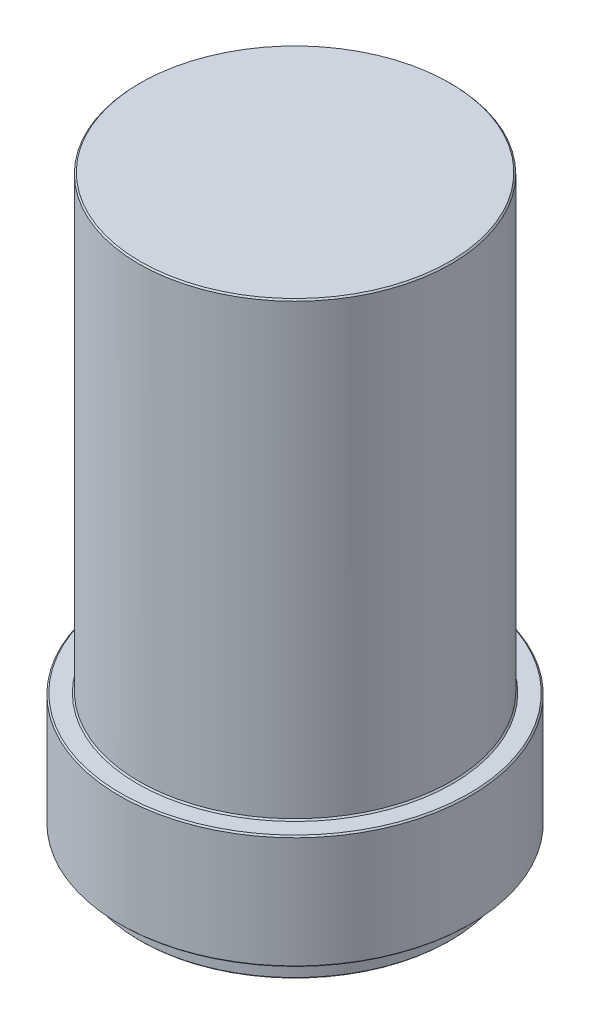
SolidWorks part; units mm, degrees
ref_plane "Front Plane" through (0, 0, 0) normal (0, 0, 1) x (1, 0, 0)
ref_plane "Top Plane" through (0, 0, 0) normal (0, 1, 0) x (1, 0, 0)
ref_plane "Right Plane" through (0, 0, 0) normal (1, 0, 0) x (0, 0, -1)
sketch "Sketch1" plane through (0, 0, 0) normal (0, 1, 0) x (1, 0, 0)
  circle A0 centre (0, 0) radius 22.5
  dimension "D1" = 45
extrude "Boss-Extrude1" add sketch "Sketch1" along normal blind 65
sketch "Sketch2" plane through (0, 0, 0) normal (0, -1, 0) x (1, 0, 0)
  circle A0 centre (0, 0) radius 25.3
  dimension "D1" = 50.6
extrude "Boss-Extrude2" add sketch "Sketch2" along normal blind 16.4
sketch "Sketch3" plane through (0, -16.4, 0) normal (0, -1, 0) x (1, 0, 0)
  circle A0 centre (0, 0) radius 22.4
  dimension "D1" = 44.8
extrude "Boss-Extrude3" add sketch "Sketch3" along normal blind 3.5
chamfer "Chamfer1" distance 0.2 angle 45 6 edges at (0, -16.4, -25.3) (0, -16.4, -22.4) (0, -19.9, -22.4) (0, 0, -25.3) (0, 0, 22.5) (0, 65, 22.5)
